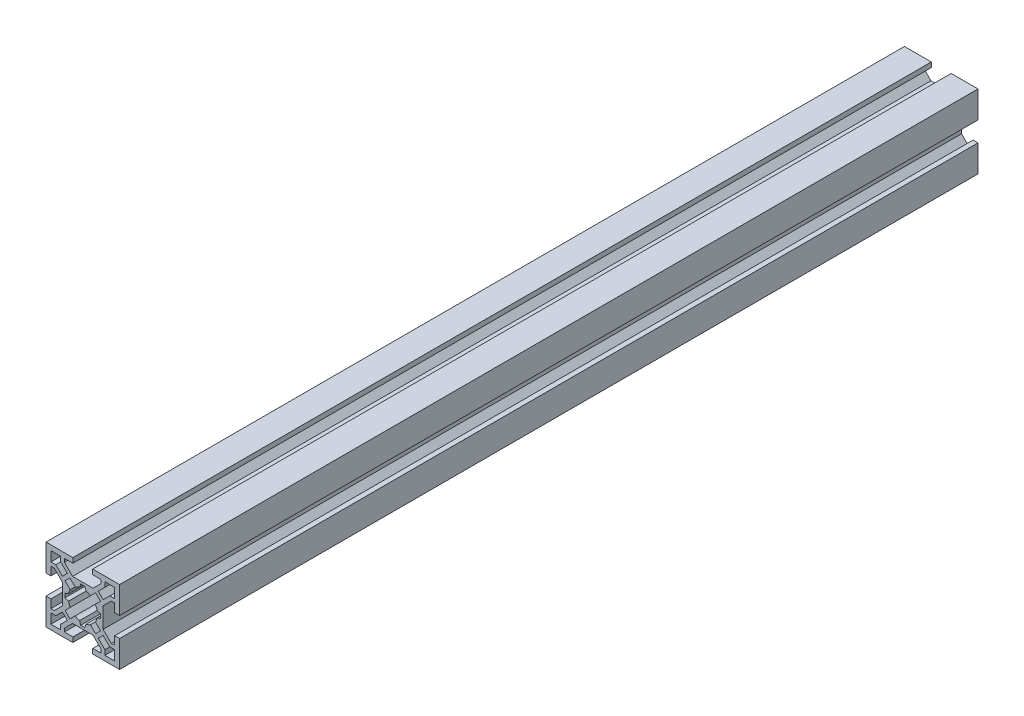
SolidWorks part; units mm, degrees
material "Liga 1060"
ref_plane "Plano frontal" through (0, 0, 0) normal (0, 0, 1) x (1, 0, 0)
ref_plane "Plano superior" through (0, 0, 0) normal (0, 1, 0) x (1, 0, 0)
ref_plane "Plano direito" through (0, 0, 0) normal (1, 0, 0) x (0, 0, -1)
ref_plane "Plano1" through (0, 0, 100) normal (0, 0, 1) x (1, 0, 0)
sketch "Esboço1" plane through (0, 0, 0) normal (0, 0, 1) x (1, 0, 0)
  line L0 (0, 0) -> (-15, -15) construction
  line L1 (-13, -4.05) -> (-15, -4.05)
  line L2 (-11.6273, -7.5) -> (-8.3, -4.1727)
  line L3 (-15, -15) -> (-4.05, -15)
  line L4 (-11.6273, -7.5) -> (-13, -7.5)
  line L5 (-7.5, -13) -> (-4.05, -13)
  line L6 (-7.2393, -5.2334) -> (-5.1254, -3.1194)
  line L7 (-8.3, -4.1727) -> (-8.3, 4.1727)
  line L8 (-11.006, -9) -> (-13, -9)
  line L9 (-13, -13) -> (-9, -13)
  line L10 (-13, -13) -> (-13, -9)
  line L11 (-13, -7.5) -> (-13, -4.05)
  line L12 (-15, -15) -> (-15, -4.05)
  line L13 (0, 0) -> (0, -8.3) construction
  line L14 (0, 0) -> (-8.3, 0) construction
  line L15 (7.2393, -5.2334) -> (5.2334, -7.2393)
  line L16 (4.05, -13) -> (4.05, -15)
  line L17 (-9, -11.006) -> (-9, -13)
  line L18 (0, 0) -> (0, 7.3) construction
  line L19 (7.5, -11.6273) -> (4.1727, -8.3)
  line L20 (7.5, -11.6273) -> (7.5, -13)
  line L21 (5.2334, -7.2393) -> (3.1194, -5.1254)
  line L22 (9, -11.006) -> (9, -13)
  line L23 (15, -15) -> (15, -4.05)
  line L24 (13, -7.5) -> (13, -4.05)
  line L25 (13, -13) -> (13, -9)
  line L26 (13, -13) -> (9, -13)
  line L27 (11.006, -9) -> (13, -9)
  line L28 (-4.1727, -8.3) -> (4.1727, -8.3)
  line L29 (8.3, -4.1727) -> (8.3, 4.1727)
  line L30 (7.2393, -5.2334) -> (5.1254, -3.1194)
  line L31 (7.5, -13) -> (4.05, -13)
  line L32 (11.6273, -7.5) -> (13, -7.5)
  line L33 (15, -15) -> (4.05, -15)
  line L34 (11.6273, -7.5) -> (8.3, -4.1727)
  line L35 (13, -4.05) -> (15, -4.05)
  line L36 (-7.2393, 5.2334) -> (-5.2334, 7.2393)
  line L37 (-4.05, 13) -> (-4.05, 15)
  line L38 (-7.5, 11.6273) -> (-4.1727, 8.3)
  line L39 (-7.5, 11.6273) -> (-7.5, 13)
  line L40 (-5.2334, 7.2393) -> (-3.1194, 5.1254)
  line L41 (13, 4.05) -> (15, 4.05)
  line L42 (11.6273, 7.5) -> (8.3, 4.1727)
  line L43 (15, 15) -> (4.05, 15)
  line L44 (11.6273, 7.5) -> (13, 7.5)
  line L45 (7.5, 13) -> (4.05, 13)
  line L46 (7.2393, 5.2334) -> (5.1254, 3.1194)
  line L47 (-5.2334, -7.2393) -> (-3.1194, -5.1254)
  line L48 (-4.1727, 8.3) -> (4.1727, 8.3)
  line L49 (11.006, 9) -> (13, 9)
  line L50 (13, 13) -> (9, 13)
  line L51 (13, 13) -> (13, 9)
  line L52 (13, 7.5) -> (13, 4.05)
  line L53 (15, 15) -> (15, 4.05)
  line L54 (9, 11.006) -> (9, 13)
  line L55 (5.2334, 7.2393) -> (3.1194, 5.1254)
  line L56 (-7.5, -11.6273) -> (-7.5, -13)
  line L57 (7.5, 11.6273) -> (7.5, 13)
  line L58 (7.5, 11.6273) -> (4.1727, 8.3)
  line L59 (-9, 11.006) -> (-9, 13)
  line L60 (-7.5, -11.6273) -> (-4.1727, -8.3)
  line L61 (4.05, 13) -> (4.05, 15)
  line L62 (7.2393, 5.2334) -> (5.2334, 7.2393)
  line L63 (-15, 15) -> (-15, 4.05)
  line L64 (-13, 7.5) -> (-13, 4.05)
  line L65 (-13, 13) -> (-13, 9)
  line L66 (-13, 13) -> (-9, 13)
  line L67 (-11.006, 9) -> (-13, 9)
  line L68 (-7.2393, 5.2334) -> (-5.1254, 3.1194)
  line L69 (-4.05, -13) -> (-4.05, -15)
  line L70 (-7.5, 13) -> (-4.05, 13)
  line L71 (-11.6273, 7.5) -> (-13, 7.5)
  line L72 (-15, 15) -> (-4.05, 15)
  line L73 (-11.6273, 7.5) -> (-8.3, 4.1727)
  line L74 (-13, 4.05) -> (-15, 4.05)
  line L75 (-6.294, -8.3) -> (-8.3, -6.294)
  line L76 (-6.294, -8.3) -> (-9, -11.006)
  line L77 (-8.3, -6.294) -> (-11.006, -9)
  line L78 (-8.3, 6.294) -> (-11.006, 9)
  line L79 (-6.294, 8.3) -> (-8.3, 6.294)
  line L80 (-6.294, 8.3) -> (-9, 11.006)
  line L81 (6.294, 8.3) -> (9, 11.006)
  line L82 (6.294, 8.3) -> (8.3, 6.294)
  line L83 (8.3, 6.294) -> (11.006, 9)
  line L84 (6.294, -8.3) -> (9, -11.006)
  line L85 (6.294, -8.3) -> (8.3, -6.294)
  line L86 (8.3, -6.294) -> (11.006, -9)
  line L87 (5.8582, -1.2966) -> (7.3, -0.8598)
  line L88 (7.3, -0.8598) -> (7.3, 0.8598)
  line L89 (5.8582, 1.2966) -> (7.3, 0.8598)
  line L90 (-1.2966, -5.8582) -> (-0.8598, -7.3)
  line L91 (-0.8598, -7.3) -> (0.8598, -7.3)
  line L92 (1.2966, -5.8582) -> (0.8598, -7.3)
  line L93 (1.2966, 5.8582) -> (0.8598, 7.3)
  line L94 (0.8598, 7.3) -> (-0.8598, 7.3)
  line L95 (-1.2966, 5.8582) -> (-0.8598, 7.3)
  line L96 (-5.8582, 1.2966) -> (-7.3, 0.8598)
  line L97 (-7.3, 0.8598) -> (-7.3, -0.8598)
  line L98 (-5.8582, -1.2966) -> (-7.3, -0.8598)
  line L99 (-7.2393, -5.2334) -> (-5.2334, -7.2393)
  arc A0 (-5.1254, -3.1194) -> (-5.8582, -1.2966) centre (0, 0) cw
  arc A1 (5.1254, -3.1194) -> (5.8582, -1.2966) centre (0, 0) ccw
  arc A2 (-3.1194, 5.1254) -> (-1.2966, 5.8582) centre (0, 0) cw
  arc A3 (-3.1194, -5.1254) -> (-1.2966, -5.8582) centre (0, 0) ccw
  arc A4 (1.2966, -5.8582) -> (3.1194, -5.1254) centre (0, 0) ccw
  arc A5 (5.8582, 1.2966) -> (5.1254, 3.1194) centre (0, 0) ccw
  arc A6 (1.2966, 5.8582) -> (3.1194, 5.1254) centre (0, 0) cw
  arc A7 (-5.8582, 1.2966) -> (-5.1254, 3.1194) centre (0, 0) cw
  point P4 (6.2364, 6.2364)
  point P6 (-6.2364, -6.2364)
  point P17 (6.2364, -6.2364)
  point P41 (-6.2364, 6.2364)
  point P60 (8.3, 0)
  point P85 (-7.297, -7.297)
  point P109 (0, 7.3)
  point P111 (7.3, 0)
  point P112 (0, 0)
  point P115 (0, -7.3)
  point P118 (-7.3, 0)
  point P119 (0, 0)
  dimension "D2" = 6
  dimension "D1" = 2
  dimension "D3" = 5.8368
  dimension "D4" = 1.5
  dimension "D5" = 1.5
  dimension "D6" = 1
  dimension "D7" = 1.7196
  dimension "D8" = 2.5933
extrude "Ressalto-extrusão1" add sketch "Esboço1" against normal mid plane 350
sketch "Esboço2" plane through (0, 0, 0) normal (0, 1, 0) x (1, 0, 0)
  circle A0 centre (0, 0) radius 4
  dimension "D1" = 8
extrude "Corte-extrusão1" [suppressed] cut sketch "Esboço2" against normal through all and the other way through all
